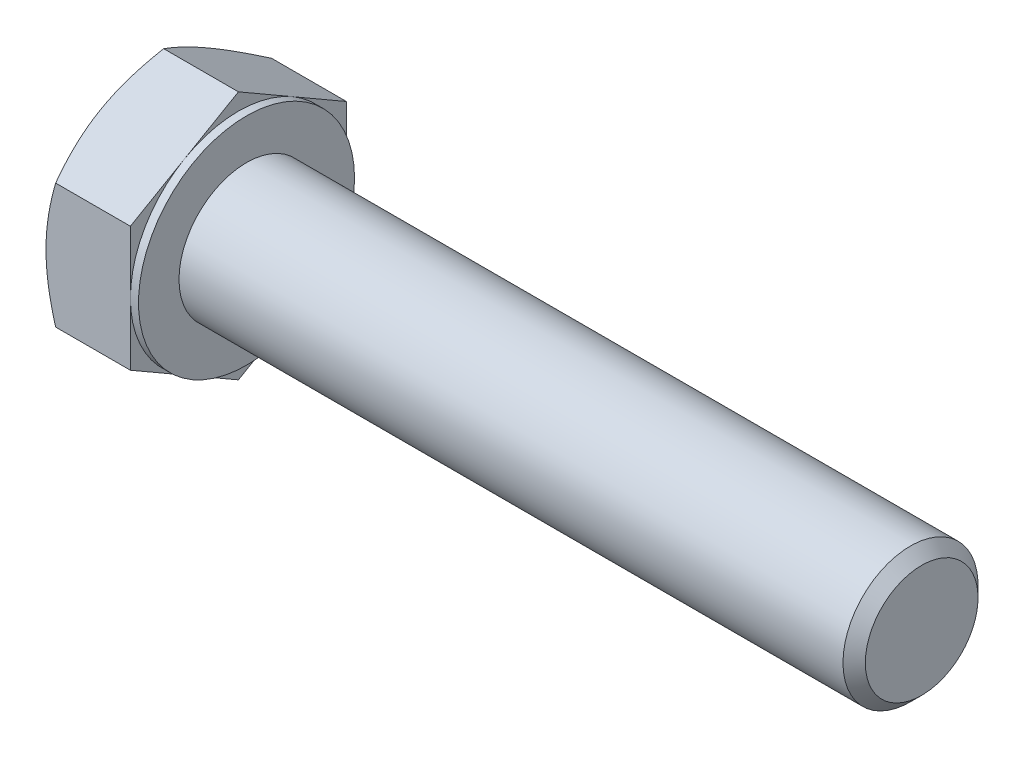
SolidWorks part; units mm, degrees
ref_plane "Plane1" through (0, 0, 0) normal (0, 0, 1) x (1, 0, 0)
ref_plane "Plane2" through (0, 0, 0) normal (0, 1, 0) x (1, 0, 0)
ref_plane "Plane3" through (0, 0, 0) normal (1, 0, 0) x (0, 0, -1)
sketch "Sketch1" plane through (0, 0, 0) normal (1, 0, 0) x (0, 0, -1)
  line L0 (8, 4.6188) -> (8, -4.6188)
  line L1 (-8, 4.6188) -> (-8, -4.6188)
  line L2 (8, -4.6188) -> (0, -9.2376)
  line L3 (0, -9.2376) -> (-8, -4.6188)
  line L4 (8, 4.6188) -> (0, 9.2376)
  line L5 (0, 9.2376) -> (-8, 4.6188)
  dimension "Width_flats" = 16
  dimension "D2" = 120
  dimension "D3" = 8
  dimension "D4" = 8
  dimension "D5" = 8
extrude "BaseHead" add sketch "Sketch1" along normal blind 6.85
sketch "BodySke" plane through (0, 0, 0) normal (0, 0, 1) x (1, 0, 0)
  line L0 (0, 4.6188) -> (0, -4.6188) construction
  line L1 (0, 0) -> (56.85, 0)
  line L2 (0, 0) -> (0, 5)
  line L3 (0, 5) -> (56.022, 5)
  line L4 (56.85, 0) -> (56.85, 4.172)
  line L5 (6.85, 9.2376) -> (6.85, 4.6188) construction
  line L6 (56.85, 4.172) -> (56.022, 5)
  line L7 (0, 0) -> (96.52, 0) construction
  line L8 (56.85, -4.172) -> (56.022, -5) construction
  line L9 (0, -5) -> (56.022, -5) construction
  line L10 (8.35, 15.24) -> (8.35, -1.27) construction
  line L11 (30.85, 15.24) -> (30.85, -1.27) construction
  line L12 (6.85, 4.6188) -> (6.85, -4.6188) construction
  dimension "Length" = 50
  dimension "Body_ch_ang" = 45
  dimension "Diameter" = 10
  dimension "Minor_dia" = 8.344
  dimension "Advance" = 1.5
  dimension "Thread_nom" = 26
revolve "BaseBody" add sketch "BodySke"
cosmetic thread "ThreadCosmetic" [suppressed]
fillet "HeadFillet" [suppressed] radius 0.4
sketch "Sketch3" plane through (0, 0, 0) normal (0, 0, 1) x (1, 0, 0)
  line L0 (0, 8) -> (3.6013, 14.2376)
  line L1 (0, 9.2376) -> (0, 4.6188) construction
  line L2 (3.6013, 14.2376) -> (3.6013, 19.2376)
  line L3 (3.6013, 19.2376) -> (-10, 19.2376)
  line L4 (-10, 19.2376) -> (-10, 8)
  line L5 (-10, 8) -> (0, 8)
  line L6 (0, 0) -> (99.06, 0) construction
  line L7 (6.85, 9.2376) -> (0, 9.2376) construction
  dimension "D1" = 8
  dimension "D2" = 5
  dimension "D3" = 10
  dimension "D4" = 5
  dimension "Head_ch_ang" = 30
revolve "HeadChamfer" cut sketch "Sketch3" angle 360 about L6
sketch "Sketch4" plane through (0, 0, 0) normal (0, 0, 1) x (1, 0, 0)
  line L1 (6.85, 9.2376) -> (6.85, 4.6188) construction
  line L2 (6.85, 8) -> (6.25, 8)
  line L3 (6.85, 8) -> (6.85, 19.2376)
  line L4 (6.85, 19.2376) -> (6.25, 19.2376)
  line L5 (0, 0) -> (95.25, 0) construction
  line L6 (0, 0) -> (96.52, 0) construction
  line L7 (6.25, 8) -> (6.25, 19.2376)
  line L8 (6.85, 9.2376) -> (0.7145, 9.2376) construction
  dimension "D1" = 16
  dimension "D2" = 10
  dimension "Bearing_ht" = 0.6
revolve "BearingFace" cut sketch "Sketch4" angle 360 about L5
sketch "ThdSchSke" plane through (0, 0, 0) normal (0, 0, 1) x (1, 0, 0)
  line L0 (30.85, -4.172) -> (30.2702, -5)
  line L1 (30.85, -4.172) -> (31.4298, -5)
  line L2 (31.4298, -5) -> (31.4298, -6.25)
  line L3 (-3.175, 0) -> (5.1513, 0) construction
  line L5 (31.4298, -6.25) -> (30.2702, -6.25)
  line L6 (30.2702, -6.25) -> (30.2702, -5)
  dimension "Thread_minor" = 8.344
  dimension "Diameter" = 10
  dimension "Start" = 30.85
  dimension "SideAngle" = 55
  dimension "VeeAngle" = 70
  dimension "Overcut" = 12.5
revolve "ThreadSchematic" [suppressed] cut sketch "ThdSchSke" angle 360 about L3
pattern_linear "ThdSchPat" [suppressed]
equation "\"D3@Sketch1\" = \"Width_flats@Sketch1\" / 2"
equation "\"D4@Sketch1\" = \"D3@Sketch1\""
equation "\"D5@Sketch1\" = \"D4@Sketch1\""
equation "\"Thread_minor@ThreadCosmetic\" = \"Minor_dia@BodySke\""
equation "\"D1@Sketch3\" = \"Width_flats@Sketch1\" / 2"
equation "\"D1@Sketch4\" = \"Width_flats@Sketch1\""
equation "\"Thread_length@ThreadCosmetic\" = ((sgn( (\"Length@BodySke\" - \"Advance@BodySke\" ) - \"Thread_nom@BodySke\" )-1)*( (\"Length@BodySke\" - \"Advance@BodySke\" ) - \"Thread_nom@BodySke\" ))/-2+ \"Thread_nom@BodySke\""
equation "\"Thread_minor@ThdSchSke\" = \"Minor_dia@BodySke\""
equation "\"Diameter@ThdSchSke\" = \"Diameter@BodySke\""
equation "\"Overcut@ThdSchSke\" = \"Diameter@BodySke\" * 1.25"
equation "\"Start@ThdSchSke\" = \"Head_ht@BaseHead\" + \"Length@BodySke\" - \"Thread_length@ThreadCosmetic\"  '---Non-countersunk---"
equation "\"Num_threads@ThdSchPat\" = int( \"Thread_length@ThreadCosmetic\" / \"Advance@BodySke\" + 0.999 )  + 1"
equation "\"Advance@ThdSchPat\" = \"Thread_length@ThreadCosmetic\" /  (\"Num_threads@ThdSchPat\" - 1) 'relax it"
equation "\"Num_threads@ThdSchPat\" = \"Num_threads@ThdSchPat\" - sgn( \"Num_threads@ThdSchPat\" - 1) '---chamfered tips only---"
